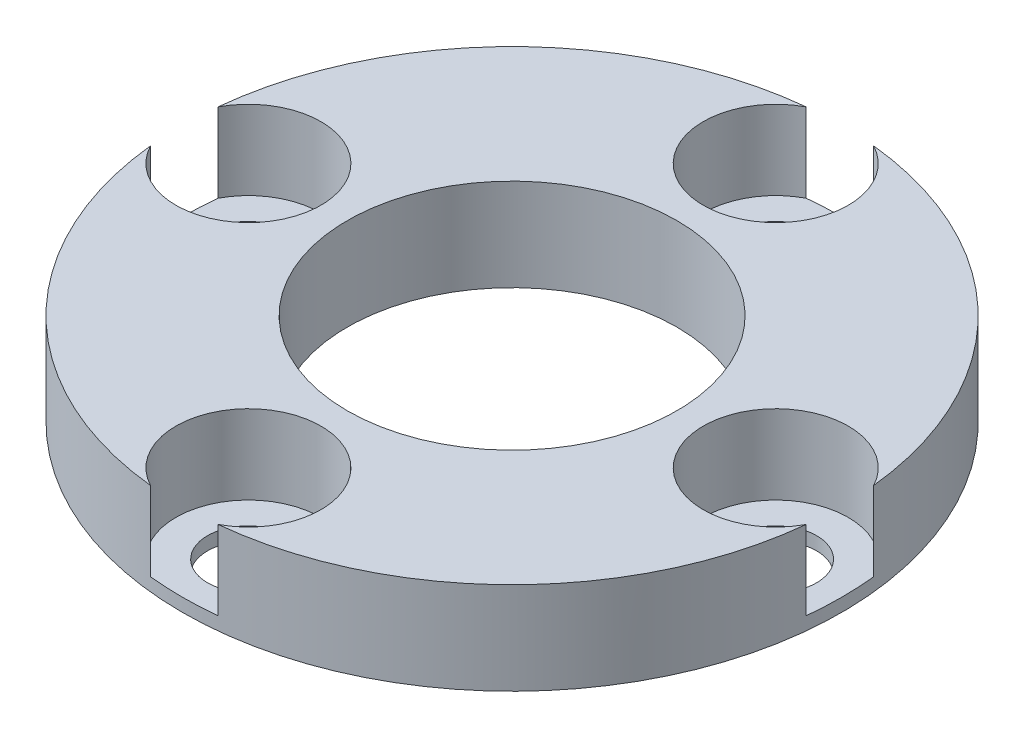
SolidWorks part; units mm, degrees
ref_plane "前视基准面" through (0, 0, 0) normal (0, 0, 1) x (1, 0, 0)
ref_plane "上视基准面" through (0, 0, 0) normal (0, 1, 0) x (1, 0, 0)
ref_plane "右视基准面" through (0, 0, 0) normal (1, 0, 0) x (0, 0, -1)
other "Configuration Table"
sketch "草图1" plane through (0, 0, 0) normal (0, 1, 0) x (1, 0, 0)
  circle A0 centre (0, 0) radius 12.5
  circle A1 centre (0, 0) radius 6.25
  dimension "D1" = 25
  dimension "D2" = 12.5
extrude "凸台-拉伸1" add sketch "草图1" along normal blind 3.5
sketch "草图2" plane through (0, 3.5, 0) normal (0, 1, 0) x (1, 0, 0)
  circle A0 centre (0, 0) radius 10 construction
  circle A1 centre (-10, 0) radius 1.55
  circle A2 centre (0, 0) radius 10 construction
  circle A3 centre (0, 10) radius 1.55
  circle A4 centre (0, 0) radius 10 construction
  circle A5 centre (10, 0) radius 1.55
  circle A6 centre (0, 0) radius 10 construction
  circle A7 centre (0, -10) radius 1.55
  point P17 (0, 0)
  dimension "D1" = 20
  dimension "D2" = 3.1
  dimension "D3" = 4
extrude "切除-拉伸1" cut sketch "草图2" against normal blind 10
sketch "草图3" plane through (0, 3.5, 0) normal (0, 1, 0) x (1, 0, 0)
  circle A0 centre (-10, 0) radius 2.75
  circle A1 centre (0, 10) radius 2.75
  circle A2 centre (10, 0) radius 2.75
  circle A3 centre (0, -10) radius 2.75
  point P12 (0, 0)
  dimension "D1" = 5.5
  dimension "D2" = 4
extrude "切除-拉伸2" cut sketch "草图3" against normal blind 3
